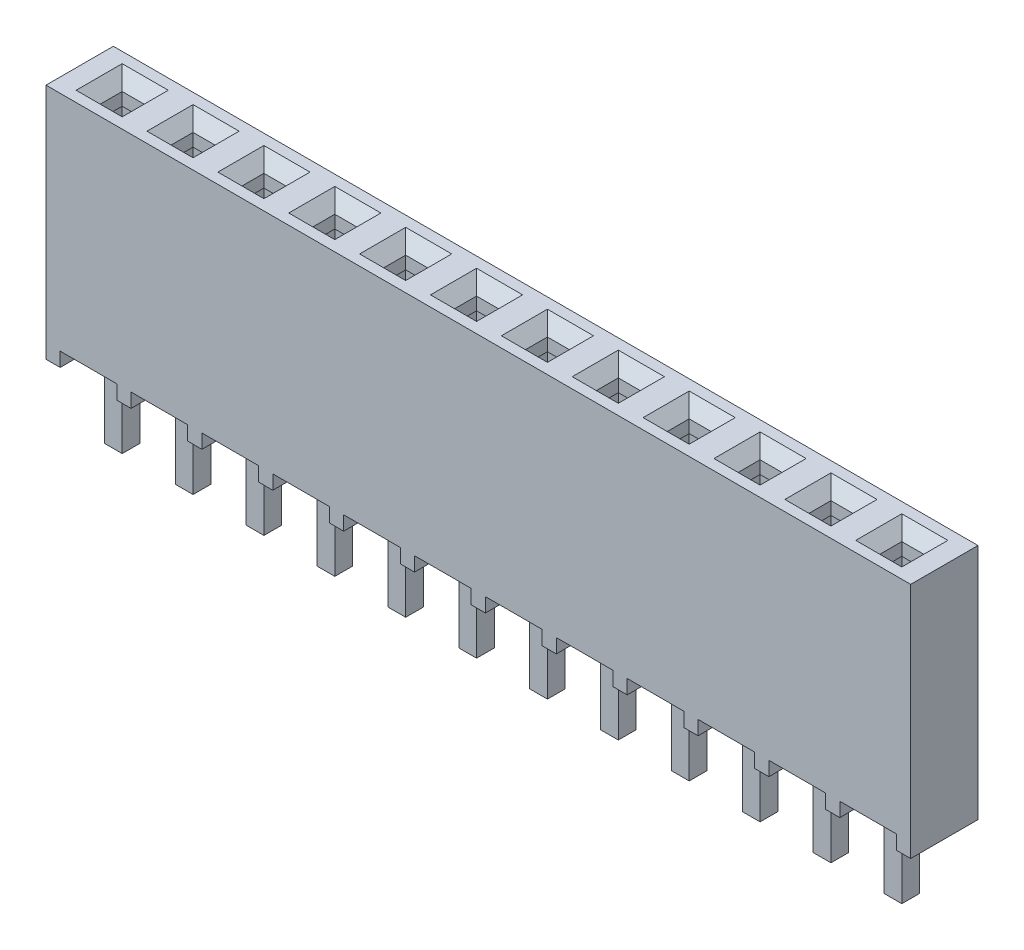
SolidWorks part; units mm, degrees
ref_plane "Front" through (0, 0, 0) normal (0, 0, 1) x (1, 0, 0)
ref_plane "Top" through (0, 0, 0) normal (0, 1, 0) x (1, 0, 0)
ref_plane "Side" through (0, 0, 0) normal (1, 0, 0) x (0, 0, -1)
sketch "Sketch1" plane through (0, 0, 0) normal (0, 1, 0) x (1, 0, 0)
  line L0 (15.494, -1.2065) -> (-15.494, 1.2065) construction
  line L1 (-15.494, 1.2065) -> (15.494, 1.2065)
  line L2 (-15.494, 1.2065) -> (-15.494, -1.2065)
  line L3 (-15.494, -1.2065) -> (15.494, -1.2065)
  line L4 (15.494, 1.2065) -> (15.494, -1.2065)
  dimension "D1" = 30.988
  dimension "D2" = 2.413
extrude "Base-Extrude" add sketch "Sketch1" against normal blind 8.509
sketch "Sketch2" plane through (0, 0, 0) normal (0, 1, 0) x (-1, 0, 0)
  line L0 (13.5763, 0) -> (14.3637, 0) construction
  line L1 (14.3637, -0.3937) -> (13.5763, -0.3937)
  line L2 (14.3637, -0.3937) -> (14.3637, 0.3937)
  line L3 (14.3637, 0.3937) -> (13.5763, 0.3937)
  line L4 (13.5763, -0.3937) -> (13.5763, 0.3937)
  line L5 (13.97, -0.3937) -> (13.97, 0.3937) construction
  line L6 (15.494, -1.2065) -> (15.494, 1.2065) construction
  line L7 (15.494, 1.2065) -> (-15.494, 1.2065) construction
  dimension "D1" = 1.2065
  dimension "D2" = 0.7874
  dimension "D3" = 0.7874
  dimension "D4" = 1.524
extrude "Opening" cut sketch "Sketch2" against normal blind 0.889
chamfer "Lead-in" distance 0.4318 angle 45 4 edges at (-14.3637, 0, 0) (-13.97, 0, 0.3937) (-13.5763, 0, 0) (-13.97, 0, -0.3937)
sketch "Sketch3" plane through (0, -0.889, 0) normal (0, 1, 0) x (-1, 0, 0)
  line L0 (13.97, 0.508) -> (13.97, -0.508) construction
  line L1 (13.462, -0.508) -> (14.478, -0.508)
  line L2 (13.462, -0.508) -> (13.462, 0.508)
  line L3 (13.462, 0.508) -> (14.478, 0.508)
  line L4 (14.478, -0.508) -> (14.478, 0.508)
  line L5 (13.462, 0) -> (14.478, 0) construction
  line L6 (13.5763, 0) -> (14.3637, 0) construction
  line L7 (13.97, -0.3937) -> (13.97, 0.3937) construction
  dimension "D1" = 1.016
  dimension "D2" = 1.016
extrude "Core" cut sketch "Sketch3" against normal through all
sketch "Sketch4" plane through (0, 0, 1.2065) normal (0, 0, 1) x (1, 0, 0)
  line L0 (-15.494, -8.509) -> (15.494, -8.509) construction
  line L1 (-14.986, -8.509) -> (-12.954, -8.509)
  line L2 (-14.986, -8.509) -> (-14.986, -8.001)
  line L3 (-14.986, -8.001) -> (-12.954, -8.001)
  line L4 (-12.954, -8.509) -> (-12.954, -8.001)
  line L5 (-13.97, -0.889) -> (-13.97, -8.001) construction
  line L6 (-14.478, -0.889) -> (-13.462, -0.889) construction
  dimension "D1" = 2.032
  dimension "D2" = 0.508
extrude "Standoff" cut sketch "Sketch4" against normal through all
pattern_linear "Body Width Pos Pattern" count 1 spacing 2.54 along (0, 1, 0) count 12 spacing 2.54 along (1, 0, 0) of "Opening", "Core", "Lead-in"
pattern_linear "Standoff Pattern" count 12 spacing 2.54 along (1, 0, 0) of "Standoff"
ref_plane "Position 1 Plane" through (0, 0, 0) normal (0, 0, -1) x (-1, 0, 0)
sketch "Sketch6" plane through (0, 0, 0) normal (0, 0, -1) x (-1, 0, 0)
  line L0 (13.6525, -8.001) -> (13.462, -8.001)
  line L1 (12.954, -8.001) -> (14.986, -8.001) construction
  line L2 (13.462, -8.001) -> (13.462, -7.366)
  line L4 (13.462, -7.366) -> (14.478, -7.366)
  line L6 (14.478, -7.366) -> (14.478, -8.001)
  line L7 (14.478, -8.001) -> (14.2875, -8.001)
  line L8 (14.2875, -8.001) -> (14.2875, -11.1506)
  line L9 (14.2875, -11.1506) -> (13.6525, -11.1506)
  line L10 (13.6525, -11.1506) -> (13.6525, -8.001)
  line L11 (13.97, -11.1506) -> (13.97, -7.366) construction
  line L12 (14.986, -8.509) -> (15.494, -8.509) construction
  line L13 (15.494, -8.509) -> (15.494, 0) construction
  dimension "D1" = 0.635
  dimension "D2" = 2.6416
  dimension "D3" = 0.635
  dimension "D4" = 1.016
  dimension "D5" = 1.524
extrude "Straight Tail" add sketch "Sketch6" along normal mid plane 0.635
chamfer "Straight Tail Tip" distance 0.1905 angle 45 4 edges at (-13.97, -11.1506, 0.3175) (-13.6525, -11.1506, 0) (-14.2875, -11.1506, 0) (-13.97, -11.1506, -0.3175)
pattern_linear "Straight Tail Pos Pattern" count 1 spacing 2.54 count 12 spacing 2.54 along (1, 0, 0) of "Straight Tail", "Straight Tail Tip"
ref_plane "Plane LL1" [suppressed] through (1.27, 0, 0) normal (-1, 0, 0) x (0, 0, 1)
ref_plane "Plane LL2" [suppressed] through (3.81, 0, 0) normal (-1, 0, 0) x (0, 0, 1)
ref_plane "-RA Pos 1 Plane" through (-13.97, 0, 0) normal (-1, 0, 0) x (0, 0, 1)
sketch "Sketch15" plane through (-13.97, 0, 0) normal (-1, 0, 0) x (0, 0, 1)
  line L0 (0.3175, -8.001) -> (0.3175, -8.9535)
  line L2 (1.0795, -9.7155) -> (1.2319, -9.7155)
  line L3 (1.0795, -10.3505) -> (1.2319, -10.3505)
  line L4 (-0.3175, -8.001) -> (-0.3175, -8.9535)
  line L5 (1.2319, -9.7155) -> (1.2319, -10.3505)
  line L6 (0.3175, -8.001) -> (-0.3175, -8.001) construction
  line L7 (1.2319, -10.033) -> (3.0266, -10.033) construction
  line L8 (1.2065, -8.509) -> (-1.2065, -8.509) construction
  line L9 (1.2065, -8.509) -> (1.2065, 0) construction
  line L10 (0, -8.001) -> (0, -7.366) construction
  line L12 (-1.2065, -8.001) -> (1.2065, -8.001) construction
  line L14 (0.508, -8.001) -> (0.3175, -8.001)
  line L15 (0.508, -8.001) -> (0.508, -7.366)
  line L16 (0.508, -7.366) -> (-0.508, -7.366)
  line L17 (-0.508, -8.001) -> (-0.508, -7.366)
  line L18 (-0.3175, -8.001) -> (-0.508, -8.001)
  arc A0 (0.3175, -8.9535) -> (1.0795, -9.7155) centre (1.0795, -8.9535) ccw
  arc A1 (-0.3175, -8.9535) -> (1.0795, -10.3505) centre (1.0795, -8.9535) ccw
  dimension "D3" = 0.762
  dimension "D2" = 1.524
  dimension "RA Tail Length" = 0.0254
  dimension "D5" = 0.635
  dimension "D6" = 1.2065
  dimension "D7" = 1.016
  dimension "D1" = 0.635
sketch "Sketch16" plane through (-13.97, 0, 0) normal (-1, 0, 0) x (0, 0, 1)
  line L0 (-2.032, -8.001) -> (-2.032, -7.366)
  line L1 (-1.2065, -8.001) -> (1.2065, -8.001) construction
  line L2 (-2.032, -7.366) -> (-3.048, -7.366)
  line L4 (-3.048, -7.366) -> (-3.048, -8.001)
  line L5 (-2.2225, -8.001) -> (-2.8575, -8.001) construction
  line L7 (-2.54, -8.001) -> (-2.54, -7.366) construction
  line L8 (-2.2225, -8.001) -> (-2.2225, -11.4935)
  line L9 (-1.4605, -12.2555) -> (1.2319, -12.2555)
  line L10 (-1.4605, -12.8905) -> (1.2319, -12.8905)
  line L11 (-2.8575, -8.001) -> (-2.8575, -11.4935)
  line L12 (1.2319, -12.2555) -> (1.2319, -12.8905)
  line L14 (1.2065, -8.509) -> (1.2065, 0) construction
  line L15 (1.2319, -12.573) -> (2.0457, -12.573) construction
  line L16 (1.2065, -8.509) -> (-1.2065, -8.509) construction
  line L17 (-2.032, -8.001) -> (-2.2225, -8.001)
  line L18 (-2.8575, -8.001) -> (-3.048, -8.001)
  arc A0 (-2.2225, -11.4935) -> (-1.4605, -12.2555) centre (-1.4605, -11.4935) ccw
  arc A1 (-2.8575, -11.4935) -> (-1.4605, -12.8905) centre (-1.4605, -11.4935) ccw
  dimension "D6" = 0.762
  dimension "D2" = 0.635
  dimension "D3" = 3.7465
  dimension "D5" = 4.064
  dimension "D7" = 1.016
  dimension "D1" = 0.635
sketch "Sketch17" plane through (-13.97, 0, 0) normal (-1, 0, 0) x (0, 0, 1)
  line L0 (-4.572, -7.366) -> (-4.572, -8.001)
  line L1 (-4.572, -8.001) -> (-4.7625, -8.001)
  line L2 (-4.7625, -8.001) -> (-4.7625, -14.0335)
  line L3 (-4.0005, -14.7955) -> (1.2319, -14.7955)
  line L4 (-4.0005, -15.4305) -> (1.2319, -15.4305)
  line L5 (-5.3975, -8.001) -> (-5.3975, -14.0335)
  line L6 (1.2319, -15.4305) -> (1.2319, -14.7955)
  line L7 (-5.3975, -8.001) -> (-5.588, -8.001)
  line L8 (-5.588, -8.001) -> (-5.588, -7.366)
  line L9 (-5.588, -7.366) -> (-4.572, -7.366)
  line L10 (-4.7625, -8.001) -> (-5.3975, -8.001) construction
  line L11 (-5.08, -8.001) -> (-5.08, -7.366) construction
  line L12 (1.2065, -8.509) -> (1.2065, 0) construction
  line L13 (1.2319, -15.113) -> (3.0224, -15.113) construction
  line L14 (1.2065, -8.509) -> (-1.2065, -8.509) construction
  line L16 (0.508, -8.001) -> (0.508, -7.366) construction
  line L17 (-1.2065, -8.001) -> (1.2065, -8.001) construction
  arc A0 (-4.7625, -14.0335) -> (-4.0005, -14.7955) centre (-4.0005, -14.0335) ccw
  arc A1 (-5.3975, -14.0335) -> (-4.0005, -15.4305) centre (-4.0005, -14.0335) ccw
  dimension "D7" = 0.762
  dimension "D2" = 0.635
  dimension "D3" = 1.016
  dimension "D5" = 6.604
  dimension "D6" = 5.08
  dimension "D1" = 0.635
sketch "Polarize" plane through (0, 0, 0) normal (0, 1, 0) x (-1, 0, 0)
  line L0 (14.7961, -0.8312) -> (13.1388, 0.8261) construction
  line L1 (14.7961, -0.8312) -> (13.1388, -0.8312)
  line L2 (14.7961, -0.8312) -> (14.7961, 0.8261)
  line L3 (14.7961, 0.8261) -> (13.1388, 0.8261)
  line L4 (13.1388, -0.8312) -> (13.1388, 0.8261)
  line L5 (13.1388, -0.8312) -> (13.9675, -0.0025) construction
  line L7 (13.97, 0.6857) -> (13.97, 2.3139) construction
  line L9 (13.462, 0) -> (14.478, 0) construction
  line L10 (15.494, -1.2065) -> (15.494, 1.2065) construction
  dimension "D1" = 1.6573
  dimension "D2" = 1.524
  dimension "Length" = 0.0025
  dimension "Width" = 0.0025
sketch "Sketch24" plane through (-15.494, 0, 0) normal (-1, 0, 0) x (0, 0, 1)
  line L0 (-1.2065, -3.0226) -> (-1.2065, -4.8006)
  line L1 (-1.2065, -8.509) -> (-1.2065, 0) construction
  line L2 (-1.2065, -4.8006) -> (-0.8255, -4.2926)
  line L3 (-0.8255, -3.5306) -> (-1.2065, -3.0226)
  line L4 (-1.2065, -3.9116) -> (-1.3335, -3.9116) construction
  line L5 (-1.2065, 0) -> (1.2065, 0) construction
  arc A0 (-0.8255, -4.2926) -> (-0.8255, -3.5306) centre (-1.3335, -3.9116) ccw
  dimension "D1" = 0.635
  dimension "D2" = 0.508
  dimension "D3" = 3.9116
  dimension "D4" = 1.778
